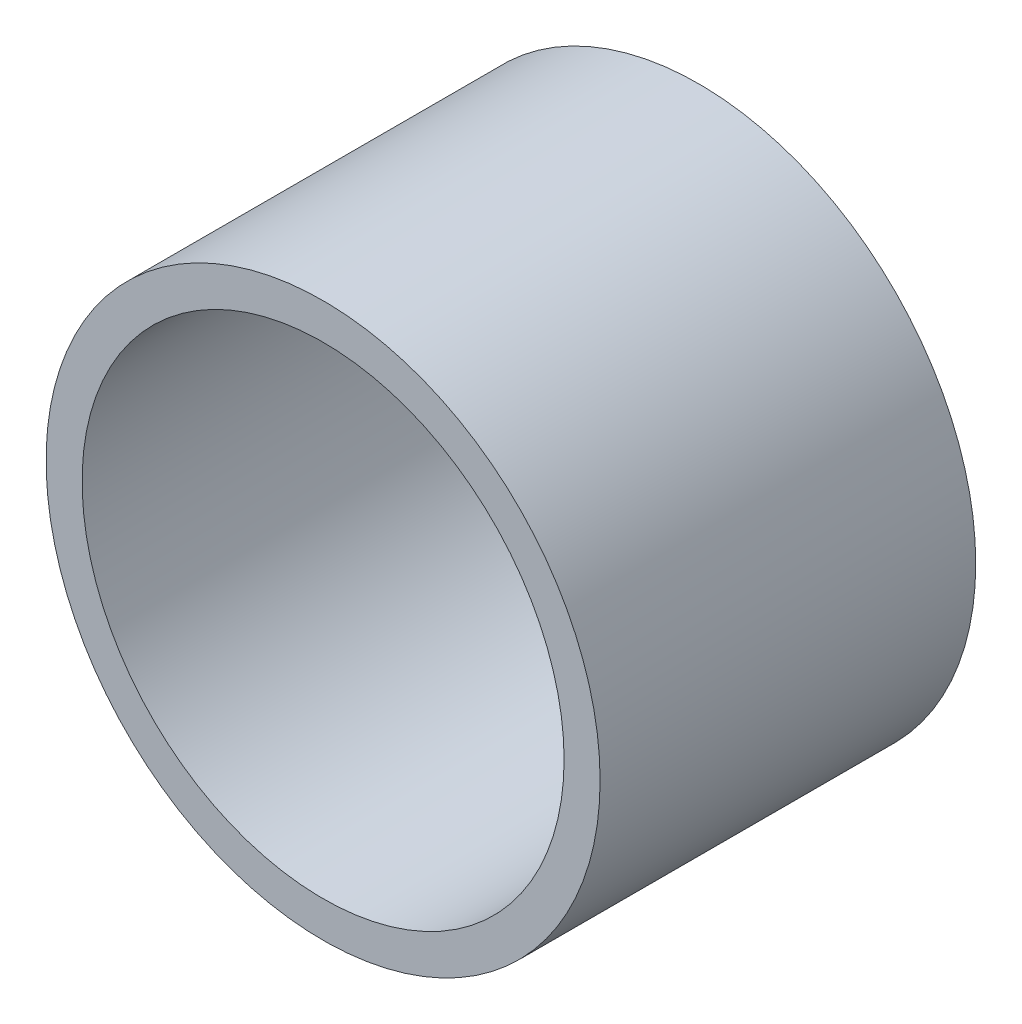
SolidWorks part; units mm, degrees
ref_plane "Front Plane" through (0, 0, 0) normal (0, 0, 1) x (1, 0, 0)
ref_plane "Top Plane" through (0, 0, 0) normal (0, 1, 0) x (1, 0, 0)
ref_plane "Right Plane" through (0, 0, 0) normal (1, 0, 0) x (0, 0, -1)
sketch "Sketch1" plane through (0, 0, 0) normal (0, 0, 1) x (1, 0, 0)
  circle A0 centre (0, 0) radius 50
  circle A1 centre (0, 0) radius 43.5
  dimension "D1" = 87
  dimension "D2" = 100
extrude "Boss-Extrude1" add sketch "Sketch1" along normal blind 67.8
